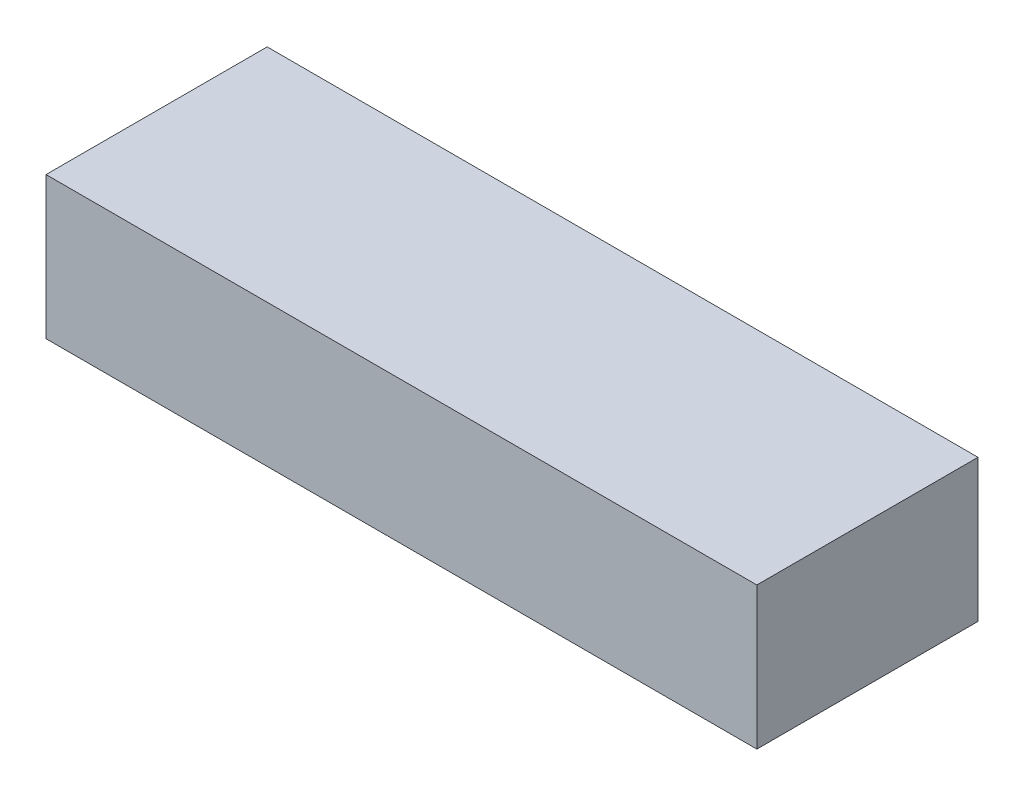
SolidWorks part; units mm, degrees
ref_plane "Front Plane" through (0, 0, 0) normal (0, 0, 1) x (1, 0, 0)
ref_plane "Top Plane" through (0, 0, 0) normal (0, 1, 0) x (1, 0, 0)
ref_plane "Right Plane" through (0, 0, 0) normal (1, 0, 0) x (0, 0, -1)
sketch "Sketch1" plane through (0, 0, 0) normal (0, 1, 0) x (1, 0, 0)
  line L1 (0, 0) -> (135, 0)
  line L2 (0, 0) -> (0, 42)
  line L3 (0, 42) -> (135, 42)
  line L4 (135, 0) -> (135, 42)
extrude "Boss-Extrude1" add sketch "Sketch1" along normal blind 27
